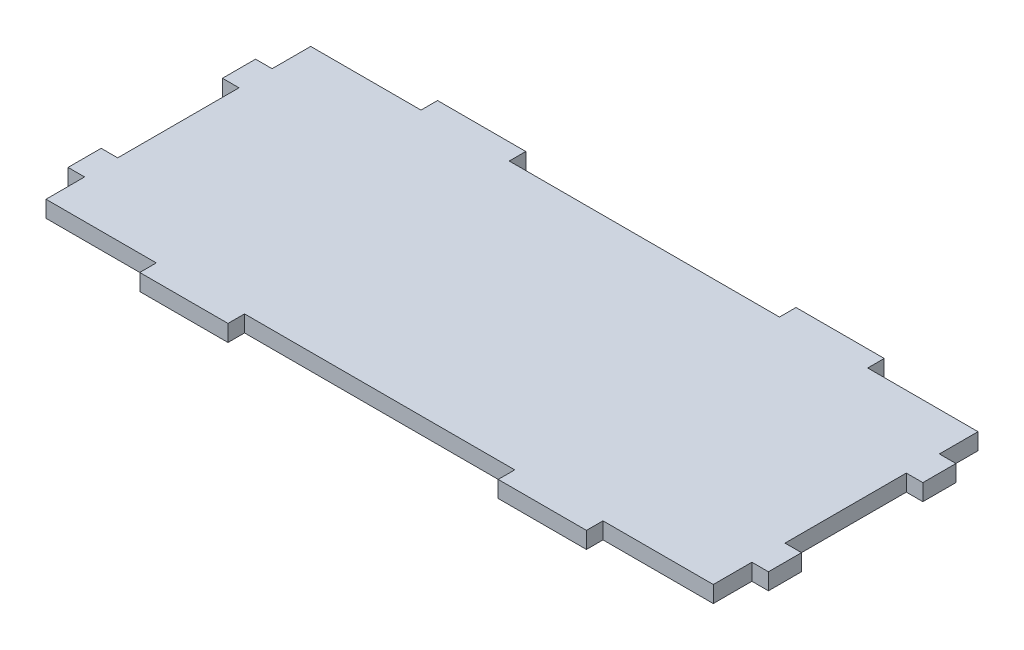
SolidWorks part; units mm, degrees
ref_plane "Front Plane" through (0, 0, 0) normal (0, 0, 1) x (1, 0, 0)
ref_plane "Top Plane" through (0, 0, 0) normal (0, 1, 0) x (1, 0, 0)
ref_plane "Right Plane" through (0, 0, 0) normal (1, 0, 0) x (0, 0, -1)
sketch "Sketch1" plane through (0, 0, 0) normal (0, 1, 0) x (1, 0, 0)
  line L0 (60.5, 48) -> (60.5, 0) construction
  line L1 (0, 0) -> (121, 0)
  line L2 (0, 0) -> (0, 48)
  line L3 (0, 48) -> (121, 48)
  line L4 (121, 0) -> (121, 48)
  line L5 (0, 41) -> (-3, 41)
  line L6 (0, 41) -> (0, 35)
  line L7 (0, 35) -> (-3, 35)
  line L8 (-3, 41) -> (-3, 35)
  line L9 (0, 13) -> (-3, 13)
  line L10 (0, 13) -> (0, 7)
  line L11 (0, 7) -> (-3, 7)
  line L12 (-3, 13) -> (-3, 7)
  line L13 (20, 0) -> (36, 0)
  line L14 (20, 0) -> (20, -3)
  line L15 (20, -3) -> (36, -3)
  line L16 (36, 0) -> (36, -3)
  line L17 (101, 0) -> (85, 0)
  line L18 (101, 0) -> (101, -3)
  line L19 (101, -3) -> (85, -3)
  line L20 (85, 0) -> (85, -3)
  line L21 (124, 13) -> (124, 7)
  line L22 (121, 7) -> (124, 7)
  line L23 (121, 13) -> (121, 7)
  line L24 (121, 13) -> (124, 13)
  line L25 (124, 41) -> (124, 35)
  line L26 (121, 35) -> (124, 35)
  line L27 (121, 41) -> (121, 35)
  line L28 (121, 41) -> (124, 41)
  line L30 (20, 51) -> (36, 51)
  line L31 (20, 51) -> (20, 48)
  line L32 (20, 48) -> (36, 48)
  line L33 (36, 51) -> (36, 48)
  line L34 (85, 51) -> (101, 51)
  line L35 (85, 51) -> (85, 48)
  line L36 (85, 48) -> (101, 48)
  line L37 (101, 51) -> (101, 48)
  dimension "D1" = 48
  dimension "D2" = 121
  dimension "D3" = 6
  dimension "D4" = 3
  dimension "D5" = 6
  dimension "D6" = 3
  dimension "D7" = 3
  dimension "D8" = 16
  dimension "D9" = 3
  dimension "D10" = 16
  dimension "D11" = 20
  dimension "D12" = 20
  dimension "D13" = 7
  dimension "D14" = 7
extrude "Boss-Extrude1" add sketch "Sketch1" along normal blind 3 contours L0 L3 L2 L1 | L3 L0 L1 L4 | L9 L12 L11 L2 | L16 L1 L14 L15 | L1 L20 L19 L18 | L28 L4 L26 L25 | L24 L4 L22 L21 | L8 L7 L6 L5 | L31 L30 L33 L32 | L35 L34 L37 L36
